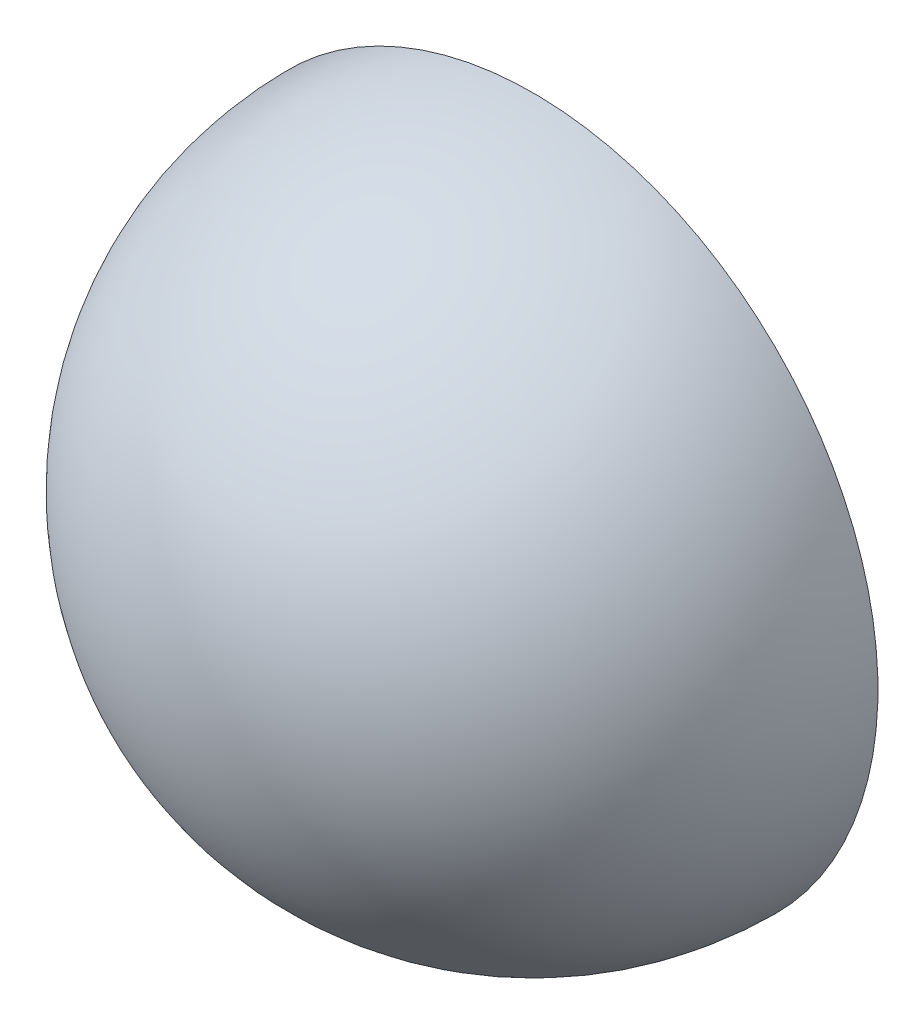
SolidWorks part; units mm, degrees
ref_plane "Front Plane" through (0, 0, 0) normal (0, 0, 1) x (1, 0, 0)
ref_plane "Top Plane" through (0, 0, 0) normal (0, 1, 0) x (1, 0, 0)
ref_plane "Right Plane" through (0, 0, 0) normal (1, 0, 0) x (0, 0, -1)
sketch "Sketch2" plane through (0, 0, 0) normal (0, 0, 1) x (1, 0, 0)
  line L0 (0, 436) -> (0, -436) construction
  line L1 (0, 436) -> (0, -436)
  arc A0 (0, -436) -> (0, 436) centre (0, 0) ccw
  arc A1 (0, -433) -> (0, 433) centre (0, 0) ccw
  dimension "D1" = 872
  dimension "D2" = 866
revolve "Revolve4" add sketch "Sketch2" angle 180 about L0
